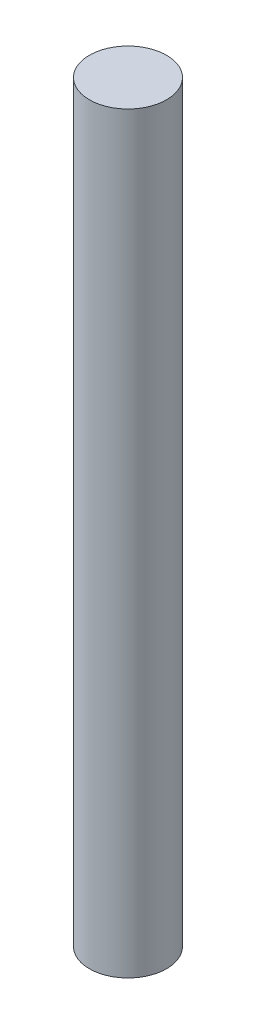
SolidWorks part; units mm, degrees
ref_plane "Front Plane" through (0, 0, 0) normal (0, 0, 1) x (1, 0, 0)
ref_plane "Top Plane" through (0, 0, 0) normal (0, 1, 0) x (1, 0, 0)
ref_plane "Right Plane" through (0, 0, 0) normal (1, 0, 0) x (0, 0, -1)
sketch "Sketch1" plane through (0, 0, 0) normal (0, 1, 0) x (1, 0, 0)
  circle A0 centre (0, 0) radius 2
  dimension "D1" = 4
extrude "Boss-Extrude1" add sketch "Sketch1" along normal blind 39
